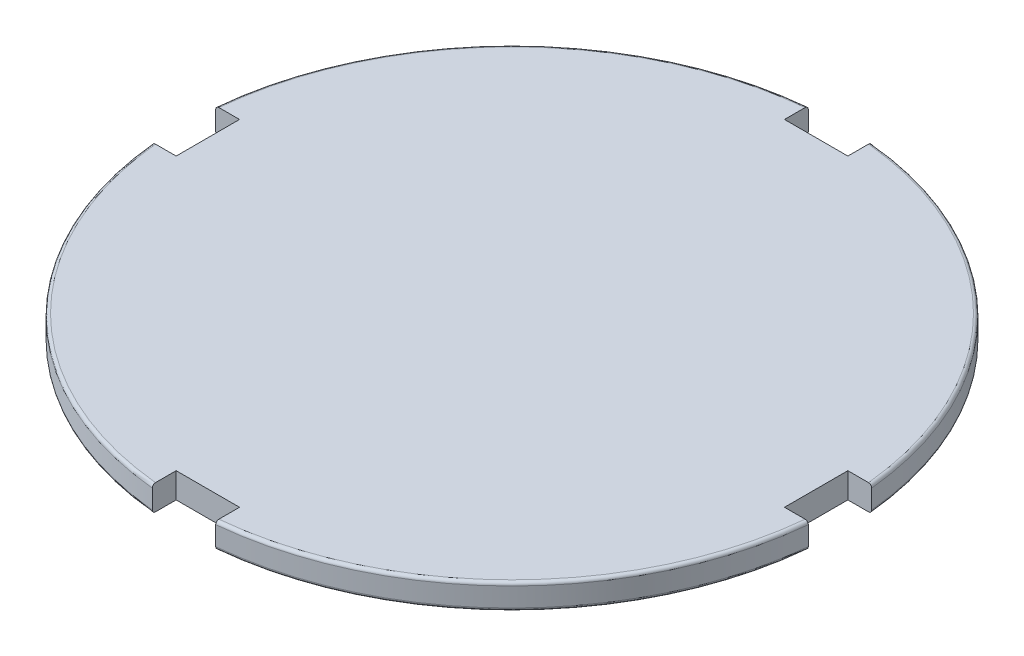
SolidWorks part; units mm, degrees
ref_plane "Front" through (0, 0, 0) normal (0, 0, 1) x (1, 0, 0)
ref_plane "Top" through (0, 0, 0) normal (0, 1, 0) x (1, 0, 0)
ref_plane "Right" through (0, 0, 0) normal (1, 0, 0) x (0, 0, -1)
sketch "Sketch2" plane through (0, 0, 0) normal (0, 1, 0) x (1, 0, 0)
  circle A0 centre (0, 0) radius 66.04
  dimension "D1" = 132.08
extrude "Boss-Extrude1" add sketch "Sketch2" along normal blind 5.08
fillet "Fillet1" radius 0.635 2 edges at (0, 0, 66.04) (0, 5.08, 66.04)
sketch "Sketch3" plane through (0, 0, 0) normal (0, -1, 0) x (1, 0, 0)
  line L0 (75.9093, 0) -> (-75.3573, 0) construction
  line L1 (0, -77.1055) -> (0, 79.4978) construction
  line L2 (13.8937, 0) -> (13.8937, 60.96) construction
  line L3 (-6.35, 76.1854) -> (6.35, 76.1854)
  line L4 (6.35, 76.1854) -> (6.35, 60.96)
  line L5 (6.35, 60.96) -> (-6.35, 60.96)
  line L6 (-6.35, 60.96) -> (-6.35, 76.1854)
  line L7 (60.96, 6.35) -> (76.1854, 6.35)
  line L8 (76.1854, 6.35) -> (76.1854, -6.35)
  line L9 (76.1854, -6.35) -> (60.96, -6.35)
  line L10 (60.96, -6.35) -> (60.96, 6.35)
  line L11 (6.35, -60.96) -> (6.35, -76.1854)
  line L12 (6.35, -76.1854) -> (-6.35, -76.1854)
  line L13 (-6.35, -76.1854) -> (-6.35, -60.96)
  line L14 (-6.35, -60.96) -> (6.35, -60.96)
  line L15 (-60.96, -6.35) -> (-76.1854, -6.35)
  line L16 (-76.1854, -6.35) -> (-76.1854, 6.35)
  line L17 (-76.1854, 6.35) -> (-60.96, 6.35)
  line L18 (-60.96, 6.35) -> (-60.96, -6.35)
  point P10 (0, 76.1854)
  point P27 (0, 0)
  dimension "D1" = 60.96
  dimension "D2" = 6.35
  dimension "D3" = 4
extrude "Cut-Extrude1" cut sketch "Sketch3" against normal through all
